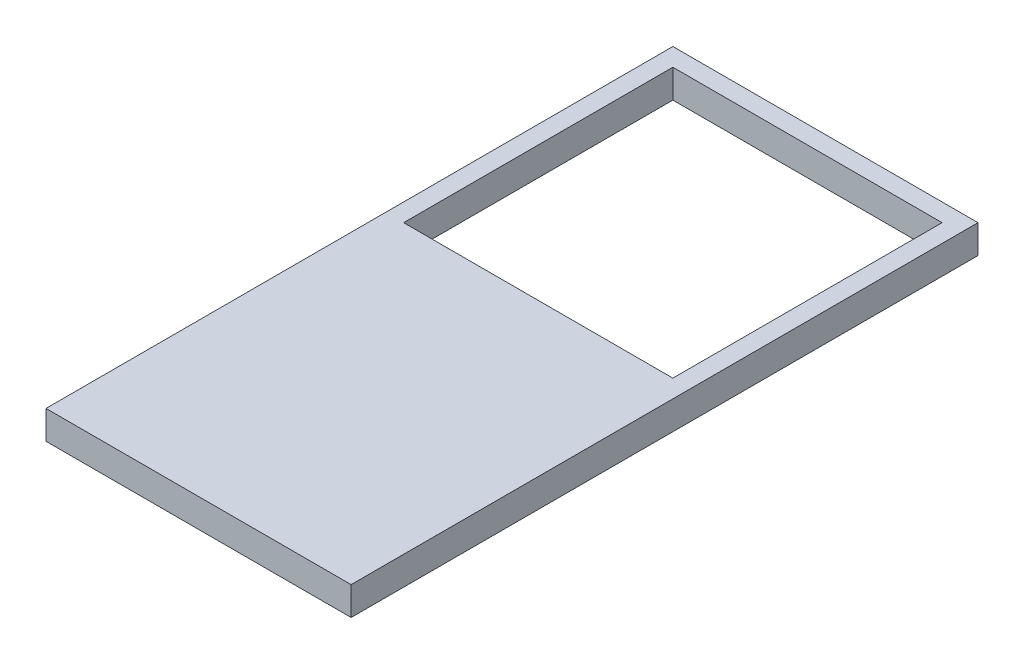
SolidWorks part; units mm, degrees
ref_plane "Front Plane" through (0, 0, 0) normal (0, 0, 1) x (1, 0, 0)
ref_plane "Top Plane" through (0, 0, 0) normal (0, 1, 0) x (1, 0, 0)
ref_plane "Right Plane" through (0, 0, 0) normal (1, 0, 0) x (0, 0, -1)
sketch "Sketch1" plane through (0, 0, 0) normal (0, 0, 1) x (1, 0, 0)
  line L1 (0, 0) -> (17, 0)
  line L2 (0, 0) -> (0, 1.5875)
  line L3 (0, 1.5875) -> (17, 1.5875)
  line L4 (17, 0) -> (17, 1.5875)
  dimension "D1" = 1.5875
  dimension "D2" = 17
extrude "Boss-Extrude1" add sketch "Sketch1" along normal blind 34.925 contours L3 L4 L1 L2
sketch "Sketch2" plane through (0, 1.5875, 0) normal (0, 1, 0) x (1, 0, 0)
  line L0 (8.5, 0) -> (8.5, -34.925) construction
  line L1 (1, -1) -> (16, -1)
  line L2 (1, -1) -> (1, -16)
  line L3 (1, -16) -> (16, -16)
  line L4 (16, -1) -> (16, -16)
  line L5 (1, -1) -> (16, -16) construction
  line L6 (1, -16) -> (16, -1) construction
  line L7 (0, 0) -> (17, 0) construction
  line L8 (0, -34.925) -> (17, -34.925) construction
  point P0 (8.5, -8.5)
  dimension "D1" = 15
  dimension "D2" = 15
  dimension "D3" = 1
extrude "Cut-Extrude1" cut sketch "Sketch2" against normal through all
